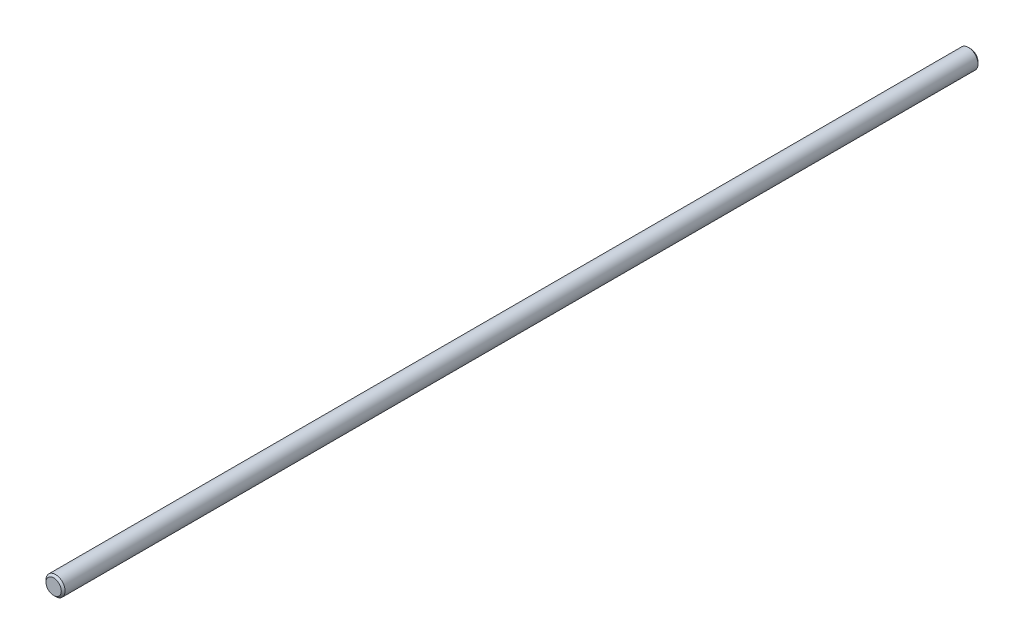
SolidWorks part; units mm, degrees
ref_plane "Front" through (0, 0, 0) normal (0, 0, 1) x (1, 0, 0)
ref_plane "Top" through (0, 0, 0) normal (0, 1, 0) x (1, 0, 0)
ref_plane "Right" through (0, 0, 0) normal (1, 0, 0) x (0, 0, -1)
sketch "Sketch1" plane through (0, 0, 0) normal (0, 0, 1) x (1, 0, 0)
  circle A0 centre (0, 0) radius 2.3813
  dimension "dia" = 4.7625
sketch "Sketch2" plane through (0, 0, 0) normal (1, 0, 0) x (0, 0, -1)
  line L0 (-114.3, 0) -> (114.3, 0) construction
  line L1 (5.2388, 0) -> (-5.2388, 0) construction
  line L3 (114.3, 2.3812) -> (114.3, -2.3813) construction
  line L4 (-114.3, 2.3813) -> (-114.3, -2.3812) construction
  line L5 (-95.25, 2.3813) -> (-95.25, -2.3813) construction
  line L6 (95.25, 2.3813) -> (95.25, -2.3813) construction
  point P6 (0, 0)
  point P10 (114.3, 0)
  point P13 (-114.3, 0)
  point P16 (-95.25, 0)
  point P19 (95.25, 0)
  dimension "D1" = 4.7625
  dimension "lg" = 228.6
  dimension "D2" = 19.05
  dimension "D3" = 19.05
sketch "Sketch3" plane through (0, 0, 0) normal (0, 0, 1) x (1, 0, 0)
  line L0 (0, 2.3813) -> (0, -2.3812) construction
  circle A0 centre (0, 0) radius 2.3813
  dimension "D1" = 4.7625
extrude "Boss-Extrude1" add sketch "Sketch3" along normal mid plane 228.6
chamfer "Chamfer1" distance 0.4763 angle 45 2 edges at (2.3813, 0, -114.3) (2.3813, 0, 114.3)
equation "\"D1@Sketch2\"=\"dia@sketch1\""
equation "\"D1@Sketch3\"=\"dia@Sketch1\""
equation "\"D1@Boss-Extrude1\"=\"lg@Sketch2\""
equation "\"D1@Chamfer1\"=\"dia@Sketch1\"*.1"
